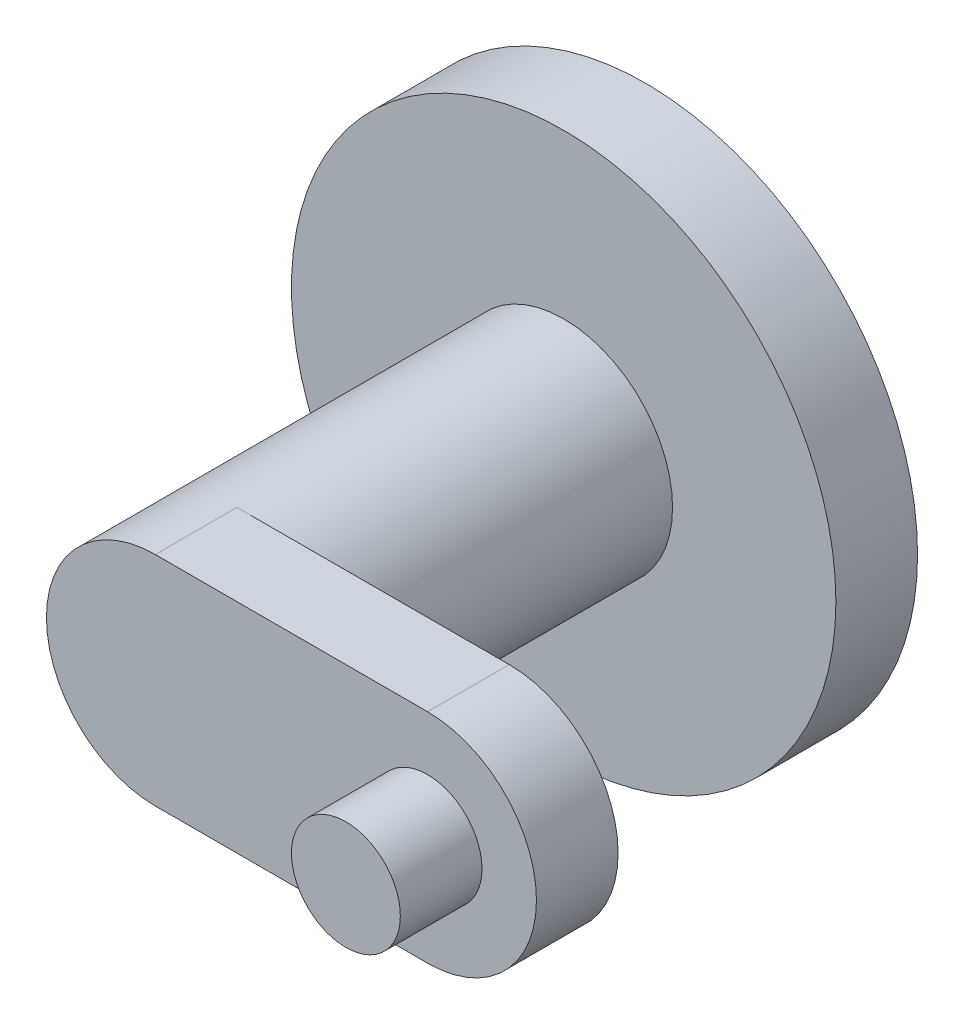
SolidWorks part; units mm, degrees
ref_plane "Front Plane" through (0, 0, 0) normal (0, 0, 1) x (1, 0, 0)
ref_plane "Top Plane" through (0, 0, 0) normal (0, 1, 0) x (1, 0, 0)
ref_plane "Right Plane" through (0, 0, 0) normal (1, 0, 0) x (0, 0, -1)
sketch "Sketch2" plane through (0, 0, 0) normal (0, 0, 1) x (1, 0, 0)
  circle A4 centre (0, 0) radius 100
  dimension "D1" = 200
extrude "Boss-Extrude1" add sketch "Sketch2" along normal blind 30
sketch "Sketch3" plane through (0, 0, 30) normal (0, 0, 1) x (1, 0, 0)
  circle A0 centre (0, 0) radius 40
  dimension "D1" = 80
extrude "Boss-Extrude2" add sketch "Sketch3" along normal blind 150
sketch "Sketch4" plane through (0, 0, 180) normal (0, 0, 1) x (1, 0, 0)
  line L0 (0, 40) -> (0, -40)
  arc A0 (0, -40) -> (0, 40) centre (0, 0) ccw
  dimension "D1" = 80
extrude "Cut-Extrude1" cut sketch "Sketch4" against normal blind 30
sketch "Sketch5" plane through (0, 0, 150) normal (0, 0, 1) x (1, 0, 0)
  line L1 (0, 40) -> (100, 40)
  line L2 (0, 40) -> (0, -40)
  line L3 (0, -40) -> (100, -40)
  arc A0 (100, -40) -> (100, 40) centre (100, 0) ccw
  circle A1 centre (100, 0) radius 20
  arc M6 (0, -40) -> (0, 40) centre (0, 0) ccw
  dimension "D3" = 40
  dimension "D1" = 80
  dimension "D2" = 100
extrude "Boss-Extrude6" add sketch "Sketch5" along normal blind 30 contours A1 | L3 A0 L1 A1 M6
sketch "Sketch6" plane through (0, 0, 180) normal (0, 0, 1) x (1, 0, 0)
  circle A0 centre (100, 0) radius 20
  dimension "D1" = 40
  dimension "D2" = 100
extrude "Boss-Extrude7" add sketch "Sketch6" along normal blind 30
sketch "Sketch10" plane through (0, 0, 0) normal (0, 0, -1) x (1, 0, 0)
  point P0 (0, 0)
